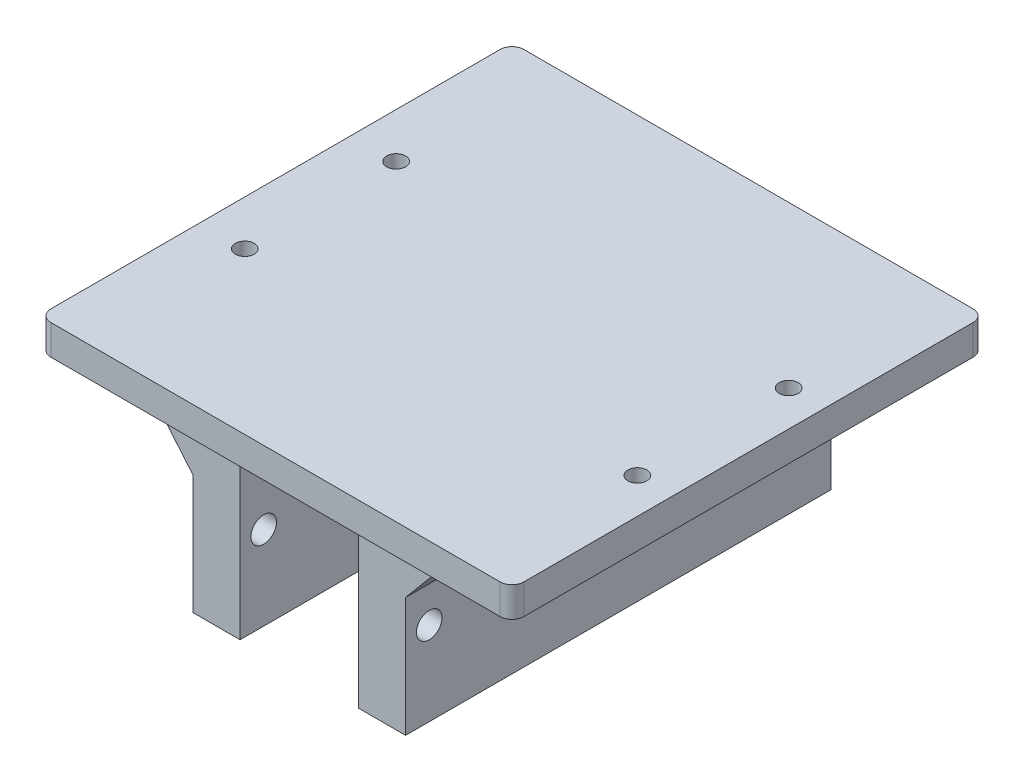
SolidWorks part; units mm, degrees
ref_plane "Front Plane" through (0, 0, 0) normal (0, 0, 1) x (1, 0, 0)
ref_plane "Top Plane" through (0, 0, 0) normal (0, 1, 0) x (1, 0, 0)
ref_plane "Right Plane" through (0, 0, 0) normal (1, 0, 0) x (0, 0, -1)
sketch "Sketch1" plane through (0, 0, 0) normal (0, 1, 0) x (1, 0, 0)
  line L1 (2.5, 0) -> (97.5, 0)
  line L2 (0, 2.5) -> (0, 97.5)
  line L3 (2.5, 100) -> (97.5, 100)
  line L4 (100, 2.5) -> (100, 97.5)
  circle A0 centre (9.5, 34) radius 2
  circle A1 centre (9.5, 66) radius 2
  arc A4 (97.5, 100) -> (100, 97.5) centre (97.5, 97.5) cw
  arc A5 (97.5, 0) -> (100, 2.5) centre (97.5, 2.5) ccw
  arc A6 (2.5, 0) -> (0, 2.5) centre (2.5, 2.5) cw
  arc A7 (0, 97.5) -> (2.5, 100) centre (2.5, 97.5) cw
  circle A8 centre (92.5, 66) radius 2
  circle A9 centre (92.5, 34) radius 2
  point P17 (100, 100)
  point P22 (0, 0)
  point P25 (0, 100)
  dimension "D1" = 4
  dimension "D7" = 2.5
  dimension "D8" = 83
  dimension "D2" = 100
  dimension "D3" = 100
  dimension "D4" = 32
  dimension "D5" = 34
  dimension "D6" = 9.5
extrude "Boss-Extrude1" add sketch "Sketch1" along normal blind 6.35
sketch "Sketch4" plane through (0, 0, 0) normal (0, 1, 0) x (1, 0, 0)
  line L0 (37.5, 50) -> (62.5, 50) construction
  line L1 (27.5, 5) -> (37.5, 5)
  line L2 (27.5, 5) -> (27.5, 95)
  line L3 (27.5, 95) -> (37.5, 95)
  line L4 (37.5, 5) -> (37.5, 95)
  line L5 (62.5, 95) -> (72.5, 95)
  line L6 (62.5, 95) -> (62.5, 5)
  line L7 (62.5, 5) -> (72.5, 5)
  line L8 (72.5, 95) -> (72.5, 5)
  line L9 (50, 100) -> (50, 0) construction
  line L10 (97.5, 100) -> (2.5, 100) construction
  line L11 (2.5, 0) -> (97.5, 0) construction
  point P16 (50, 50)
  point P17 (50, 50)
  dimension "D1" = 25
  dimension "D2" = 5
  dimension "D3" = 10
extrude "Boss-Extrude2" add sketch "Sketch4" against normal blind 36.75
sketch "Sketch5" plane through (27.5, 0, 0) normal (-1, 0, 0) x (0, 0, 1)
  line L0 (-95, -36.75) -> (-95, 0) construction
  line L2 (-95, 0) -> (-5, 0) construction
  circle A0 centre (-90, -19.05) radius 2.7
  circle A1 centre (-50, -19.05) radius 2.7
  circle A2 centre (-10, -19.05) radius 2.7
  dimension "D1" = 40
  dimension "D3" = 5.4
  dimension "D2" = 80
  dimension "D4" = 5
  dimension "D5" = 19.05
extrude "Cut-Extrude1" cut sketch "Sketch5" against normal through all
draft "Draft1" [suppressed] type of draft neutral plane draft angle 5 faces to draft 6 parameters "D1"=5
sketch "Sketch6" plane through (0, 0, -5) normal (0, 0, 1) x (1, 0, 0)
  line L0 (72.5, 0) -> (82.1418, 0)
  line L1 (2.5, 0) -> (97.5, 0) construction
  line L2 (82.1418, 0) -> (72.5, -11.4907)
  line L3 (72.5, -36.75) -> (72.5, 0) construction
  line L4 (72.5, -11.4907) -> (72.5, 0)
  line L5 (27.5, 0) -> (17.8582, 0)
  line L6 (17.8582, 0) -> (27.5, -11.4907)
  line L7 (27.5, -36.75) -> (27.5, 0) construction
  line L8 (27.5, -11.4907) -> (27.5, 0)
  dimension "D1" = 15
  dimension "D2" = 50
extrude "Boss-Extrude3" add sketch "Sketch6" against normal up to surface (90 mm away) from surface at 0 up to face at (32.5, -18.375, -95) starting at face at (32.5, -18.375, -5)
